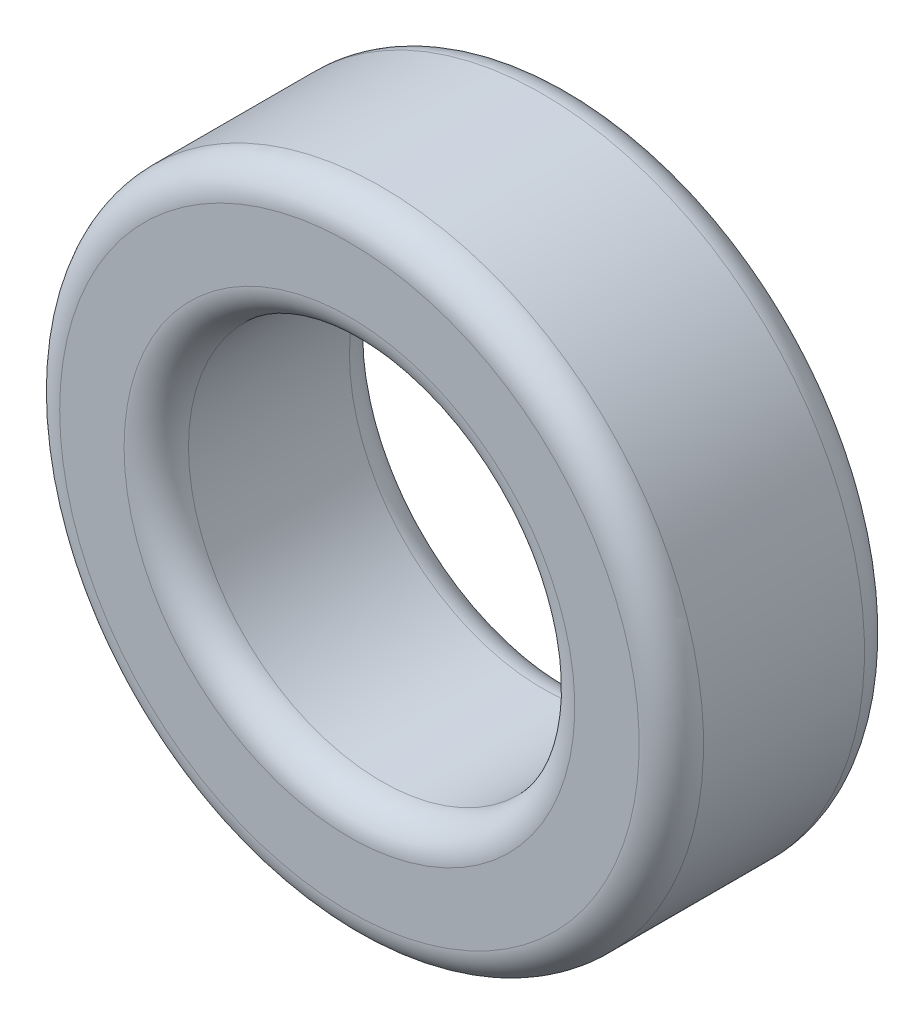
SolidWorks part; units mm, degrees
material "ASTM A36"
ref_plane "Plano frontal" through (0, 0, 0) normal (0, 0, 1) x (1, 0, 0)
ref_plane "Plano superior" through (0, 0, 0) normal (0, 1, 0) x (1, 0, 0)
ref_plane "Plano direito" through (0, 0, 0) normal (1, 0, 0) x (0, 0, -1)
sketch "Esboço1" plane through (0, 0, 0) normal (1, 0, 0) x (0, 0, -1)
  line L0 (0, 0) -> (-2816.5897, 0) construction
  line L1 (-1.25, 5) -> (1.25, 5)
  line L2 (-1.75, 4.5) -> (-1.75, 3.5)
  line L3 (-1.25, 3) -> (1.25, 3)
  line L4 (1.75, 4.5) -> (1.75, 3.5)
  line L5 (-1.75, 5) -> (1.75, 3) construction
  line L6 (-1.75, 3) -> (1.75, 5) construction
  arc A0 (-1.75, 3.5) -> (-1.25, 3) centre (-1.25, 3.5) ccw
  arc A1 (1.25, 3) -> (1.75, 3.5) centre (1.25, 3.5) ccw
  arc A2 (1.25, 5) -> (1.75, 4.5) centre (1.25, 4.5) cw
  arc A3 (-1.25, 5) -> (-1.75, 4.5) centre (-1.25, 4.5) ccw
  point P0 (0, 4)
  dimension "D4" = 0.5
  dimension "D1" = 6
  dimension "D2" = 10
  dimension "D3" = 3.5
revolve "Revolução1" add sketch "Esboço1" angle 360 about L0
